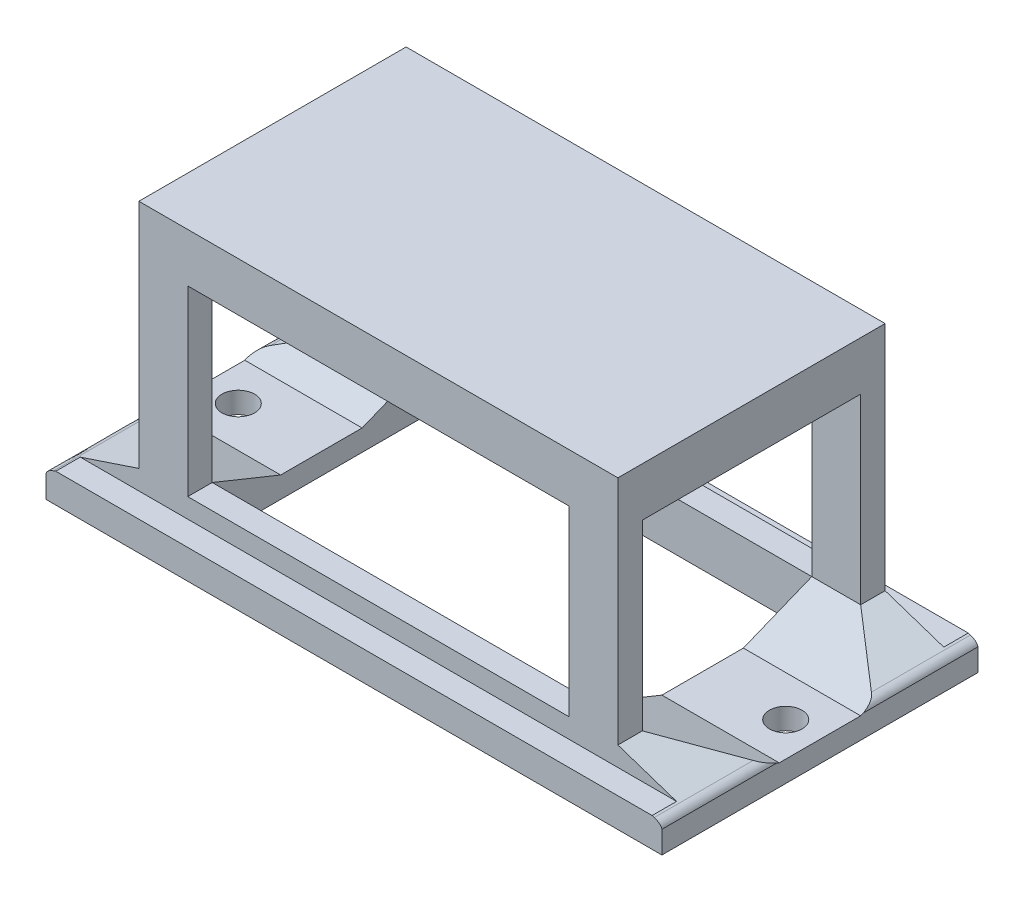
SolidWorks part; units mm, degrees
ref_plane "前视基准面" through (0, 0, 0) normal (0, 0, 1) x (1, 0, 0)
ref_plane "上视基准面" through (0, 0, 0) normal (0, 1, 0) x (1, 0, 0)
ref_plane "右视基准面" through (0, 0, 0) normal (1, 0, 0) x (0, 0, -1)
sketch "草图1" plane through (0, 0, 0) normal (0, 1, 0) x (1, 0, 0)
  line L1 (-11.7, 6.7) -> (11.7, 6.7)
  line L2 (-11.7, 6.7) -> (-11.7, -6.7)
  line L3 (-11.7, -6.7) -> (11.7, -6.7)
  line L4 (11.7, 6.7) -> (11.7, -6.7)
  line L5 (-11.7, 6.7) -> (11.7, -6.7) construction
  line L6 (-11.7, -6.7) -> (11.7, 6.7) construction
  line L7 (-14.7, 9.7) -> (14.7, 9.7)
  line L8 (-14.7, 9.7) -> (-14.7, -9.7)
  line L9 (-14.7, -9.7) -> (14.7, -9.7)
  line L10 (14.7, 9.7) -> (14.7, -9.7)
  line L11 (-14.7, 9.7) -> (14.7, -9.7) construction
  line L12 (-14.7, -9.7) -> (14.7, 9.7) construction
  point P0 (0, 0)
  point P6 (0, 0)
  dimension "D1" = 23.4
  dimension "D2" = 13.4
  dimension "D3" = 3
  dimension "D4" = 3
extrude "凸台-拉伸1" add sketch "草图1" along normal blind 16.4
sketch "草图2" plane through (0, 16.4, 0) normal (0, 1, 0) x (1, 0, 0)
  line L1 (-14.7, -9.7) -> (14.7, -9.7)
  line L2 (-14.7, -9.7) -> (-14.7, 9.7)
  line L3 (-14.7, 9.7) -> (14.7, 9.7)
  line L4 (14.7, -9.7) -> (14.7, 9.7)
  line L5 (-14.7, -9.7) -> (14.7, 9.7) construction
  line L6 (-14.7, 9.7) -> (14.7, -9.7) construction
  point P0 (0, 0)
extrude "凸台-拉伸2" add sketch "草图2" along normal blind 0.8
sketch "草图7" plane through (-14.7, 0, 0) normal (-1, 0, 0) x (0, 0, 1)
  line L0 (9.7, 8.6) -> (-9.7, 8.6)
  line L1 (9.7, 17.2) -> (9.7, 0) construction
  line L2 (-9.7, 17.2) -> (-9.7, 0) construction
  line L3 (-9.7, 0) -> (9.7, 0) construction
  line L4 (6.7, 14.2) -> (-6.7, 14.2)
  line L5 (6.7, 14.2) -> (6.7, 3)
  line L6 (6.7, 3) -> (-6.7, 3)
  line L7 (-6.7, 14.2) -> (-6.7, 3)
  line L8 (6.7, 14.2) -> (-6.7, 3) construction
  line L9 (6.7, 3) -> (-6.7, 14.2) construction
  point P6 (0, 8.6)
  dimension "D1" = 3
  dimension "D2" = 3
extrude "切除-拉伸2" cut sketch "草图7" against normal blind 30 contours L4 L7 L0 L5 | L0 L7 L6 L5
sketch "草图8" plane through (0, 0, -9.7) normal (0, 0, -1) x (-1, 0, 0)
  line L0 (-14.7, 8.6) -> (14.7, 8.6)
  line L1 (-14.7, 17.2) -> (-14.7, 0) construction
  line L2 (14.7, 17.2) -> (14.7, 0) construction
  line L3 (-14.7, 17.2) -> (14.7, 17.2) construction
  line L4 (-11.7, 14.2) -> (11.7, 14.2)
  line L5 (-11.7, 14.2) -> (-11.7, 3)
  line L6 (-11.7, 3) -> (11.7, 3)
  line L7 (11.7, 14.2) -> (11.7, 3)
  line L8 (-11.7, 14.2) -> (11.7, 3) construction
  line L9 (-11.7, 3) -> (11.7, 14.2) construction
  point P6 (0, 8.6)
  dimension "D1" = 3
  dimension "D2" = 3
extrude "切除-拉伸3" cut sketch "草图8" against normal blind 30 contours L7 L4 L5 L0 | L7 L0 L5 L6
sketch "草图9" plane through (14.7, 0, 0) normal (1, 0, 0) x (0, 0, -1)
  line L1 (9.7, 0) -> (-9.7, 0)
  line L2 (9.7, 0) -> (9.7, 3)
  line L3 (9.7, 3) -> (-9.7, 3)
  line L4 (-9.7, 0) -> (-9.7, 3)
extrude "凸台-拉伸5" add sketch "草图9" along normal blind 4.2
sketch "草图10" plane through (0, 0, 9.7) normal (0, 0, 1) x (1, 0, 0)
  line L0 (18.9, 1.3692) -> (18.9, 1.6)
  line L1 (18.9, 3) -> (18.9, 0) construction
  line L2 (18.9, 3) -> (18.9, 1.6)
  line L3 (18.4866, 1.7378) -> (14.7, 3)
  line L4 (14.7, 3) -> (18.9, 3)
  spline S0 degree 2 poles (18.4297, 1.7568) (18.8199, 1.6361) (18.9, 1.3692) knots 0 0 0 0.659175 0.659175 0.659175
  line M6 (18.9, 0) -> (18.9, 3)
  line M7 (18.9, 3) -> (14.7, 3)
extrude "切除-拉伸4" cut sketch "草图10" against normal blind 20.2 contours L3 S0 M6 M7
sketch "草图11" plane through (14.7, 0, 0) normal (1, 0, 0) x (0, 0, -1)
  line L0 (6.7, 3) -> (-6.7, 3)
  line L1 (-9.7, 0) -> (9.7, 0) construction
  line L2 (6.7, 3) -> (-6.7, 3)
  line L3 (6.7, 3) -> (6.7, 1.3)
  line L4 (6.7, 1.3) -> (-6.7, 1.3)
  line L5 (-6.7, 3) -> (-6.7, 1.3)
  line L6 (2.5, 1.3) -> (-2.5, 1.3)
  line L7 (-2.5, 1.3) -> (-6.7, 3)
  line L8 (2.5, 1.3) -> (6.7, 3)
  point P11 (0, 1.3)
  dimension "D1" = 1.3
  dimension "D2" = 5
extrude "切除-拉伸5" cut sketch "草图11" along normal mid plane 10.2 contours L4 L8 L0 L7
sketch "草图12" plane through (0, 1.3, 0) normal (0, 1, 0) x (1, 0, 0)
  line L0 (18.9, 2.5) -> (11.7, 2.5) construction
  line L1 (18.9, -2.5) -> (14.7, -2.5)
  line L2 (18.9, -2.5) -> (18.9, 2.5)
  line L3 (18.9, 2.5) -> (14.7, 2.5)
  line L4 (14.7, -2.5) -> (14.7, 2.5)
  line L5 (14.7, -9.7) -> (14.7, 9.7) construction
  circle A0 centre (16.8, 0) radius 1
  dimension "D1" = 2
extrude "切除-拉伸6" cut sketch "草图12" against normal blind 2.2 contours A0
mirror "镜向1" about plane through (0, 0, 0) normal (1, 0, 0) of "切除-拉伸5", "切除-拉伸4", "切除-拉伸6", "凸台-拉伸5"
sketch "草图13" plane through (0, 17.2, 0) normal (0, 1, 0) x (1, 0, 0)
  line L0 (14.7, 9.7) -> (14.7, 6.7) construction
  line L1 (-14.7, 9.7) -> (14.7, 9.7)
  line L3 (-14.7, 8.2) -> (14.7, 8.2)
  line L5 (-14.7, -6.7) -> (-14.7, -9.7) construction
  line L6 (14.7, -9.7) -> (-14.7, -9.7)
  line L8 (14.7, -8.2) -> (-14.7, -8.2)
  line L10 (-18.9, 2.671) -> (-18.9, 9.7) construction
  line L11 (-14.7, 9.7) -> (-18.9, 9.7)
  line L13 (-14.7, 8.2) -> (-18.9, 8.2)
  line L14 (-18.9, 9.7) -> (-18.9, 8.2)
  line L15 (18.9, 2.671) -> (18.9, 9.7) construction
  line L16 (14.7, 9.7) -> (18.9, 9.7)
  line L18 (14.7, 8.2) -> (18.9, 8.2)
  line L19 (18.9, 9.7) -> (18.9, 8.2)
  line L21 (14.7, -8.2) -> (18.9, -8.2)
  line L23 (14.7, -9.7) -> (18.9, -9.7)
  line L24 (18.9, -8.2) -> (18.9, -9.7)
  line L25 (-14.7, -8.2) -> (-18.9, -8.2)
  line L27 (-14.7, -9.7) -> (-18.9, -9.7)
  line L28 (-18.9, -8.2) -> (-18.9, -9.7)
extrude "切除-拉伸7" cut sketch "草图13" against normal blind 15.4
